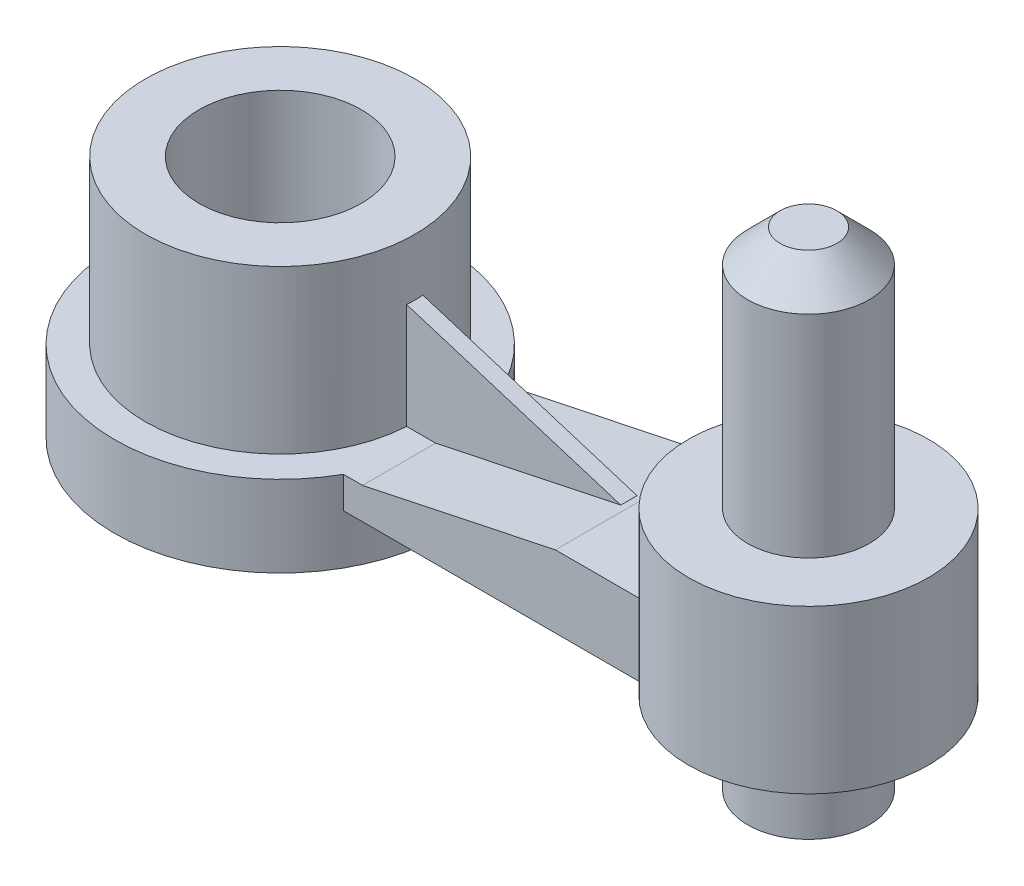
SolidWorks part; units mm, degrees
ref_plane "Alzado" through (0, 0, 0) normal (0, 0, 1) x (1, 0, 0)
ref_plane "Planta" through (0, 0, 0) normal (0, 1, 0) x (1, 0, 0)
ref_plane "Vista lateral" through (0, 0, 0) normal (1, 0, 0) x (0, 0, -1)
sketch "Croquis1" plane through (0, 0, 0) normal (0, 1, 0) x (1, 0, 0)
  circle A0 centre (-17.3198, -0.6127) radius 8.295
  circle A1 centre (-17.3198, -0.6127) radius 5
  dimension "D1" = 16.59
  dimension "D2" = 10
extrude "Saliente-Extruir1" add sketch "Croquis1" along normal blind 10
sketch "Croquis2" plane through (0, 0, 0) normal (0, -1, 0) x (1, 0, 0)
  circle A0 centre (-17.3198, 0.6127) radius 10.195
  dimension "D1" = 20.39
extrude "Saliente-Extruir2" add sketch "Croquis2" along normal blind 5
sketch "Croquis5" plane through (0, -5, 0) normal (0, -1, 0) x (1, 0, 0)
  line L0 (-17.3198, 0.6127) -> (15.2002, 0.6127) construction
  circle A0 centre (15.2002, 0.6127) radius 3.745
  dimension "D2" = 7.49
  dimension "D1" = 32.52
extrude "Saliente-Extruir3" add sketch "Croquis5" along normal mid plane 5 separate body
sketch "Croquis6" plane through (0, -2.5, 0) normal (0, 1, 0) x (1, 0, 0)
  circle A0 centre (15.2002, -0.6127) radius 7.385
  dimension "D1" = 14.77
extrude "Saliente-Extruir4" add sketch "Croquis6" along normal blind 10
sketch "Croquis7" plane through (0, -2.5, 0) normal (0, -1, 0) x (1, 0, 0)
  circle A0 centre (15.2002, 0.6127) radius 3.745
extrude "Cortar-Extruir3" cut sketch "Croquis7" against normal blind 10
sketch "Croquis8" plane through (0, -2.5, 0) normal (0, 1, 0) x (1, 0, 0)
  circle A0 centre (15.2002, -0.6127) radius 3.745
extrude "Saliente-Extruir5" add sketch "Croquis8" along normal blind 23
sketch "Croquis9" plane through (0, 20.5, 0) normal (0, 1, 0) x (1, 0, 0)
  circle A0 centre (15.2002, -0.6127) radius 3.745
extrude "Saliente-Extruir6" add sketch "Croquis9" along normal blind 2 draft 45 separate body
sketch "Croquis11" plane through (0, 22.5, 0) normal (0, 1, 0) x (1, 0, 0)
  circle A0 centre (15.2002, -0.6127) radius 1.745
ref_plane "Plano2" through (0, 0, 1) normal (0, 0, 1) x (1, 0, 0)
sketch "Croquis12" plane through (0, 0, 1) normal (0, 0, 1) x (1, 0, 0)
  line L0 (-7.1248, -5) -> (-7.1248, -1.94) construction
  line L2 (-7.1248, -5) -> (-7.1248, 0) construction
  line L3 (-7.1248, -1.94) -> (7.8152, -1.94)
  line L4 (7.8152, 7.5) -> (7.8152, -2.5) construction
  line L5 (-7.1248, 0) -> (4.6202, 2.5)
  line L6 (-7.1248, 0) -> (-27.5148, 0) construction
  line L7 (4.6202, 2.5) -> (7.8152, 2.5)
  line L9 (-7.1248, -1.94) -> (-8.479, -1.94)
  line L10 (-8.479, -1.94) -> (-8.479, 0)
  line L11 (-8.479, 0) -> (-7.1248, 0)
  line L12 (7.8152, 2.5) -> (9.9753, 2.5)
  line L13 (9.9753, 2.5) -> (9.9753, -1.94)
  line L14 (9.9753, -1.94) -> (7.8152, -1.94)
  line L15 (15.2002, 7.5) -> (15.2002, -2.5) construction
  line L16 (22.5852, 7.5) -> (7.8152, 7.5) construction
  line L17 (11.4552, -2.5) -> (18.9452, -2.5) construction
  dimension "D1" = 3.06
  dimension "D2" = 5
  dimension "D3" = 10.58
ref_plane "Plano6" through (0, 0, 0.61) normal (0, 0, 1) x (1, 0, 0)
sketch "Croquis20" plane through (0, 0, 0.61) normal (0, 0, 1) x (1, 0, 0)
  line L0 (-8.479, 0) -> (-8.479, -1.94)
  line L1 (-8.479, -1.94) -> (9.9753, -1.94)
  line L2 (9.9753, -1.94) -> (9.9753, 2.5)
  line L3 (9.9753, 2.5) -> (4.6202, 2.5)
  line L4 (4.6202, 2.5) -> (-7.1248, 0)
  line L5 (-7.1248, 0) -> (-8.479, 0)
  line L7 (15.2002, 7.5) -> (15.2002, -2.5) construction
  line L8 (22.5852, 7.5) -> (7.8152, 7.5) construction
  line L9 (11.4552, -2.5) -> (18.9452, -2.5) construction
extrude "Saliente-Extruir16" add sketch "Croquis20" along normal mid plane 10
sketch "Croquis21" plane through (0, 0, 0.61) normal (0, 0, 1) x (1, 0, 0)
  line L0 (-7.1248, 0) -> (4.1452, 2.3989)
  line L1 (-7.1248, 0) -> (4.6202, 2.5) construction
  line L2 (4.1452, 2.3989) -> (-9.0248, 6.4958)
  line L3 (-9.0248, 0) -> (-9.0248, 10) construction
  line L4 (-9.0248, 6.4958) -> (-12.1242, 7.46)
  line L8 (-12.1242, 7.46) -> (-12.1242, 0)
  line L9 (-8.4336, 0) -> (-27.5148, 0) construction
  line L10 (-12.1242, 0) -> (-7.1248, 0)
  line L11 (-27.5148, -5) -> (-7.1248, -5) construction
  dimension "D1" = 12.46
  dimension "D2" = 107.28
  dimension "D3" = 11.27
extrude "Saliente-Extruir19" add sketch "Croquis21" along normal mid plane 1
sketch "Croquis22" plane through (0, 0, 0.61) normal (0, 0, 1) x (1, 0, 0)
  line L0 (-8.4336, 0) -> (-8.4336, -1.94)
  line L1 (-8.4367, -1.94) -> (-7.1248, -1.94) construction
  line L2 (-8.4336, -1.94) -> (-8.4336, 0) construction
  line L3 (-8.4336, -1.94) -> (9.7627, -1.94)
  line L4 (9.7627, -1.94) -> (9.7627, 2.5)
  line L5 (9.7627, 2.5) -> (7.4242, 2.5)
  line L6 (-8.4336, 0) -> (-7.2574, 0)
  line L7 (-7.1248, 0) -> (-8.4336, 0) construction
  line L8 (-7.2574, 0) -> (4.6202, 2.5)
  line L9 (22.5852, 7.5) -> (7.8152, 7.5) construction
  line L10 (7.4242, 2.5) -> (4.6202, 2.5)
  line L11 (15.2002, 7.5) -> (15.2002, -2.5) construction
  line L12 (11.4552, -2.5) -> (18.9452, -2.5) construction
  dimension "D1" = 5
  dimension "D2" = 10.58
extrude "Saliente-Extruir20" add sketch "Croquis22" along normal mid plane 10
